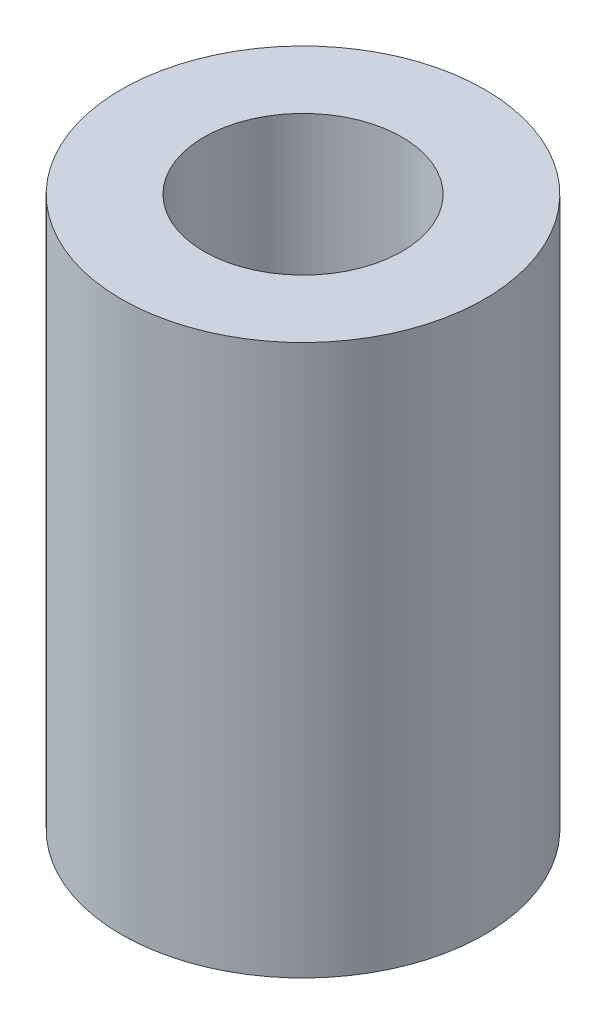
SolidWorks part; units mm, degrees
ref_plane "Front Plane" through (0, 0, 0) normal (0, 0, 1) x (1, 0, 0)
ref_plane "Top Plane" through (0, 0, 0) normal (0, 1, 0) x (1, 0, 0)
ref_plane "Right Plane" through (0, 0, 0) normal (1, 0, 0) x (0, 0, -1)
sketch "Sketch1" plane through (0, 0, 0) normal (0, 1, 0) x (1, 0, 0)
  circle A0 centre (0, 0) radius 4.572
  circle A1 centre (0, 0) radius 8.382
extrude "Boss-Extrude1" add sketch "Sketch1" along normal blind 25.4
